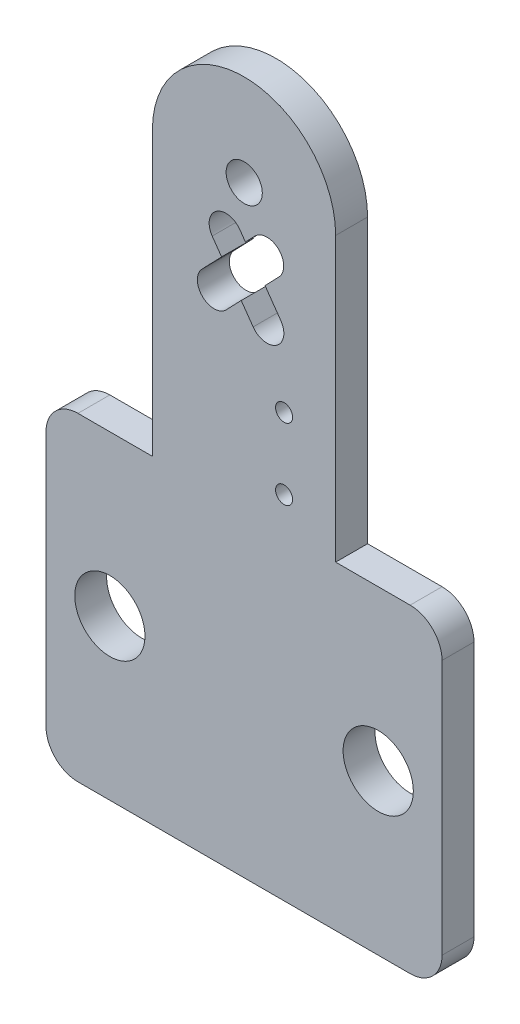
SolidWorks part; units mm, degrees
ref_plane "Front Plane" through (0, 0, 0) normal (0, 0, 1) x (1, 0, 0)
ref_plane "Top Plane" through (0, 0, 0) normal (0, 1, 0) x (1, 0, 0)
ref_plane "Right Plane" through (0, 0, 0) normal (1, 0, 0) x (0, 0, -1)
sketch "Sketch1" plane through (0, 0, 0) normal (0, 0, 1) x (1, 0, 0)
  line L5 (50.7738, 15) -> (50.7738, 41.5958)
  line L6 (50.7738, 15) -> (40.7738, 15)
  line L7 (78, -15) -> (40.7738, -15)
  line L9 (78, -15) -> (78, 15)
  line L13 (68, 15) -> (68, 41.5958)
  line L14 (78, 15) -> (68, 15)
  line L15 (40.7738, -15) -> (40.7738, 15)
  arc A0 (68, 41.5958) -> (50.7738, 41.5958) centre (59.3869, 41.5958) ccw
  point P2 (59.3869, 0)
extrude "Boss-Extrude1" add sketch "Sketch1" along normal blind 3
hole_wizard "M3 Clearance Hole1" positions "Sketch2" profile "Sketch3" hole size "M3" standard "ISO" end condition through all
sketch "Sketch2" plane through (0, 0, 3) normal (0, 0, 1) x (1, 0, 0)
  point P0 (59.4035, 41.5958)
sketch "Sketch3" plane through (59.4035, 41.5958, 3) normal (1, 0, 0) x (0, -1, 0)
  line L0 (0, 0) -> (0, 3)
  line L1 (0, 3) -> (1.7, 3)
  line L2 (1.7, 3) -> (1.7, 0)
  line L5 (1.7, 0) -> (0, 0)
  line L11 (0, -6.35) -> (0, 107.95) construction
  dimension "Thru Hole Dia." = 3.4
  dimension "Thru Hole Depth" = 3
hole_wizard "M6 Clearance Hole1" positions "Sketch4" profile "Sketch5" hole size "M6" standard "ISO" end condition through all
sketch "Sketch4" plane through (0, 0, 3) normal (0, 0, 1) x (1, 0, 0)
  line L1 (40.7738, 15) -> (40.7738, -15) construction
  line L2 (78, -15) -> (78, 15) construction
  line L3 (59.1771, -15) -> (59.1771, 15) construction
  line L4 (40.7738, -15) -> (78, -15) construction
  line L5 (59.1771, 15) -> (50.7738, 15) construction
  point P0 (46.7738, 0)
  point P4 (72, 0)
  point P21 (0, 0)
  dimension "D1" = 6
  dimension "D2" = 6
sketch "Sketch5" plane through (46.7738, 0, 3) normal (1, 0, 0) x (0, -1, 0)
  line L0 (0, 0) -> (0, 3)
  line L1 (0, 3) -> (3.3, 3)
  line L2 (3.3, 3) -> (3.3, 0)
  line L5 (3.3, 0) -> (0, 0)
  line L11 (0, -6.35) -> (0, 107.95) construction
  dimension "Thru Hole Dia." = 6.6
  dimension "Thru Hole Depth" = 3
fillet "Fillet1" radius 3 4 edges at (78, -15, 1.5) (40.7738, -15, 1.5) (40.7738, 15, 1.5) (78, 15, 1.5)
sketch "Sketch6" plane through (0, 0, 0) normal (0, 0, -1) x (-1, 0, 0)
  line L0 (-50.7738, 15) -> (-68, 15) construction
  line L1 (-59.121, 31.8633) -> (-60.2422, 30.2687)
  line L2 (-58.9921, 37.5667) -> (-59.5167, 36.8206)
  line L4 (-62.6763, 35.5621) -> (-61.3626, 34.1953)
  line L5 (-56.3948, 35.7405) -> (-57.2751, 34.4886)
  line L11 (-59.121, 31.8633) -> (-57.7117, 30.397)
  line L12 (-55.4406, 32.58) -> (-57.2751, 34.4886)
  line L14 (-59.5167, 36.8206) -> (-60.4052, 37.7451)
  line L15 (-61.3626, 34.1953) -> (-62.8394, 32.0949)
  arc A1 (-56.3948, 35.7405) -> (-58.9921, 37.5667) centre (-57.6935, 36.6536) ccw
  arc A2 (-62.8394, 32.0949) -> (-60.2422, 30.2687) centre (-61.5408, 31.1818) ccw
  arc A4 (-60.4052, 37.7451) -> (-62.6763, 35.5621) centre (-61.5408, 36.6536) ccw
  arc A5 (-57.7117, 30.397) -> (-55.4406, 32.58) centre (-56.5761, 31.4885) ccw
  point P13 (-59.6171, 33.9177)
  point P18 (-60.4638, 35.5422)
  point P20 (-59.0585, 34.071)
extrude "Cut-Extrude1" cut sketch "Sketch6" against normal blind 10
hole_wizard "Tap Drill for M2 Tap1" positions "Sketch7" profile "Sketch8" hole size "M2" standard "ISO" end condition through all
sketch "Sketch7" plane through (0, 0, 3) normal (0, 0, 1) x (1, 0, 0)
  point P0 (63.15, 24.765)
  point P3 (63.15, 18.065)
sketch "Sketch8" plane through (63.15, 24.765, 3) normal (1, 0, 0) x (0, -1, 0)
  line L0 (0, 0) -> (0, 3)
  line L1 (0, 3) -> (0.8, 3)
  line L2 (0.8, 3) -> (0.8, 0)
  line L5 (0.8, 0) -> (0, 0)
  line L11 (0, -6.35) -> (0, 107.95) construction
  dimension "Thru Hole Dia." = 1.6
  dimension "Thru Hole Depth" = 3
equation "\"D2@Sketch4\"=\"D1@Sketch4\""
